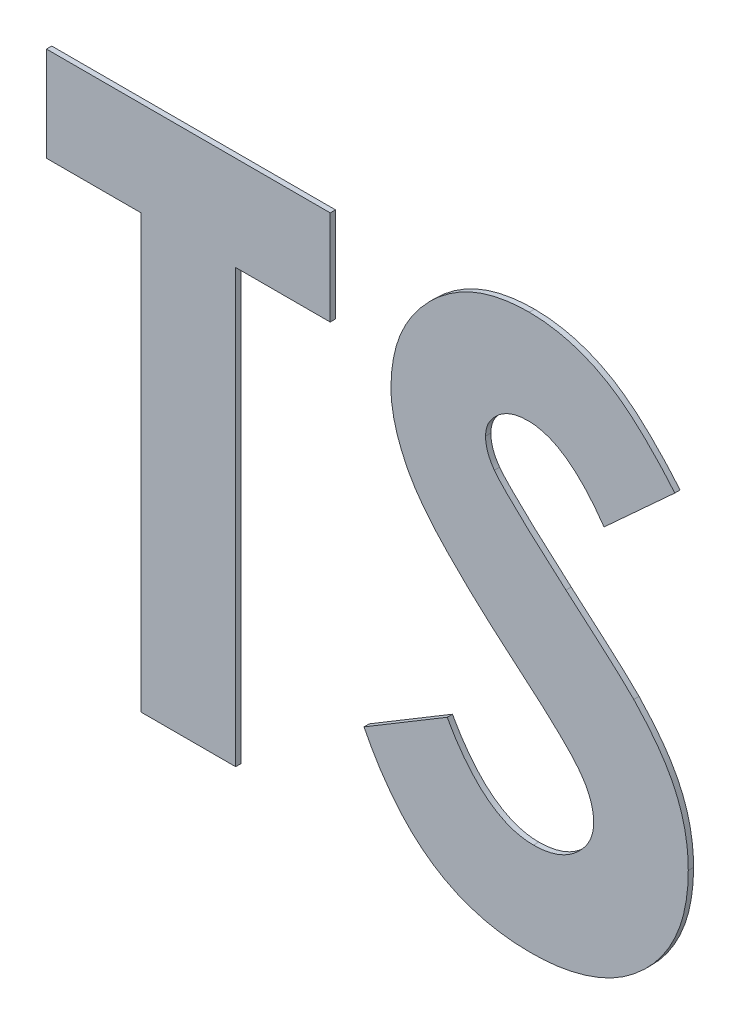
SolidWorks part; units mm, degrees
ref_plane "Front Plane" through (0, 0, 0) normal (0, 0, 1) x (1, 0, 0)
ref_plane "Top Plane" through (0, 0, 0) normal (0, 1, 0) x (1, 0, 0)
ref_plane "Right Plane" through (0, 0, 0) normal (1, 0, 0) x (0, 0, -1)
sketch "Sketch2" plane through (0, 0, 0) normal (0, 0, 1) x (1, 0, 0)
  line L0 (-12.5, 0) -> (12.5, 0)
  line L1 (-6.3462, 10) -> (-0.9615, 10)
  line L2 (-0.9615, 10) -> (-0.9615, 8.2051)
  line L3 (-0.9615, 8.2051) -> (-2.7564, 8.2051)
  line L4 (-2.7564, 8.2051) -> (-2.7564, 0)
  line L5 (-2.7564, 0) -> (-4.5513, 0)
  line L6 (-4.5513, 0) -> (-4.5513, 8.2051)
  line L7 (-4.5513, 8.2051) -> (-6.3462, 8.2051)
  line L8 (-6.3462, 8.2051) -> (-6.3462, 10)
  line L9 (5.5769, 8.6639) -> (4.2348, 7.4359)
  line L10 (-0.3205, 1.873) -> (1.258, 2.8205)
  spline S0 degree 3 poles (4.2348, 7.4359) (4.1274, 7.5935) (3.9586, 7.811) (3.7099, 8.059) (3.531, 8.2055) (3.3496, 8.3196) (3.1102, 8.4259) (2.9207, 8.4619) (2.7965, 8.4615) knots 0 0 0 0 0.311824 0.448433 0.573381 0.689077 0.797573 1 1 1 1
  spline S1 degree 3 poles (2.7965, 8.4615) (2.6872, 8.4617) (2.5244, 8.4422) (2.3335, 8.3511) (2.212, 8.2647) (2.1159, 8.1604) (2.0148, 8.0173) (1.9881, 7.8888) (1.9872, 7.8065) knots 0 0 0 0 0.285993 0.416634 0.54738 0.671583 0.784401 1 1 1 1
  spline S2 degree 3 poles (1.9872, 7.8065) (1.9859, 7.7225) (2.0179, 7.5513) (2.1012, 7.3986) (2.1534, 7.3277) knots 0 0 0 0 0.487115 1 1 1 1
  spline S3 degree 3 poles (2.1534, 7.3277) (2.2046, 7.2594) (2.3042, 7.1523) (2.4571, 6.9964) (2.6145, 6.8473) (2.7962, 6.6735) (3.0992, 6.4023) (3.34, 6.1871) (3.5116, 6.0377) knots 0 0 0 0 0.136349 0.233805 0.349411 0.483179 0.635967 1 1 1 1
  spline S4 degree 3 poles (3.5116, 6.0377) (3.6708, 5.899) (3.8991, 5.7042) (4.1821, 5.4542) (4.3571, 5.3001) (4.5049, 5.1667) (4.6501, 5.0308) (4.7456, 4.9393) (4.7997, 4.8838) knots 0 0 0 0 0.366184 0.520457 0.655012 0.770624 0.865677 1 1 1 1
  spline S5 degree 3 poles (4.7997, 4.8838) (4.972, 4.703) (5.2072, 4.4292) (5.4597, 4.0421) (5.6003, 3.7658) (5.7062, 3.4871) (5.8076, 3.0986) (5.8335, 2.7949) (5.8333, 2.5901) knots 0 0 0 0 0.289954 0.417139 0.535255 0.648751 0.762405 1 1 1 1
  spline S6 degree 3 poles (5.8333, 2.5901) (5.8366, 2.3918) (5.8074, 2.0997) (5.7236, 1.7235) (5.6289, 1.4615) (5.5132, 1.2106) (5.3683, 0.9748) (5.1982, 0.7517) (5.0031, 0.5453) (4.7874, 0.358) (4.556, 0.1913) (4.3066, 0.0536) (4.0415, -0.0597) (3.7607, -0.147) (3.3581, -0.2352) (3.0436, -0.2568) (2.8305, -0.2564) knots 0 0 0 0 0.127927 0.189047 0.248544 0.307607 0.367248 0.426963 0.488617 0.550392 0.611331 0.672556 0.734024 0.797341 0.86225 1 1 1 1
  spline S7 degree 3 poles (2.8305, -0.2564) (2.6612, -0.2563) (2.4104, -0.2415) (2.0849, -0.1877) (1.8527, -0.131) (1.6283, -0.0591) (1.4117, 0.0287) (1.2043, 0.1339) (1.0048, 0.2541) (0.8139, 0.3938) (0.6293, 0.5499) (0.4528, 0.725) (0.2836, 0.9186) (0.1228, 1.1312) (-0.0923, 1.4428) (-0.2305, 1.6979) (-0.3205, 1.873) knots 0 0 0 0 0.125868 0.18624 0.244977 0.303358 0.36123 0.418489 0.475937 0.534204 0.594059 0.655469 0.718772 0.784975 0.853522 1 1 1 1
  spline S8 degree 3 poles (1.258, 2.8205) (1.3655, 2.6242) (1.5403, 2.3522) (1.8114, 2.0406) (2.0144, 1.8585) (2.2242, 1.7157) (2.5109, 1.58) (2.7432, 1.5381) (2.8966, 1.5385) knots 0 0 0 0 0.307612 0.442139 0.566229 0.681222 0.789558 1 1 1 1
  spline S9 degree 3 poles (2.8966, 1.5385) (3.0475, 1.5373) (3.2697, 1.5716) (3.5386, 1.6928) (3.7094, 1.819) (3.8538, 1.9649) (3.9954, 2.1785) (4.0406, 2.3639) (4.0385, 2.486) knots 0 0 0 0 0.275473 0.404346 0.53543 0.661427 0.777867 1 1 1 1
  spline S10 degree 3 poles (4.0385, 2.486) (4.0382, 2.6022) (4.0031, 2.7792) (3.9021, 3.0036) (3.8111, 3.1449) (3.7183, 3.2632) (3.6297, 3.3657) (3.5217, 3.4789) (3.3947, 3.6031) (3.2503, 3.7392) (3.0239, 3.9465) (2.8406, 4.1029) (2.7123, 4.2107) knots 0 0 0 0 0.155091 0.238352 0.328404 0.379384 0.439618 0.509831 0.588875 0.677436 0.775547 1 1 1 1
  spline S11 degree 3 poles (2.7123, 4.2107) (2.4672, 4.4164) (2.1184, 4.7176) (1.6845, 5.1157) (1.4102, 5.3846) (1.1693, 5.6321) (0.9634, 5.8601) (0.7947, 6.0706) (0.6171, 6.3198) (0.4488, 6.6236) (0.2567, 7.1011) (0.1897, 7.4745) (0.1923, 7.7204) knots 0 0 0 0 0.215201 0.309902 0.395959 0.473447 0.54214 0.602523 0.654726 0.747804 0.835278 1 1 1 1
  spline S12 degree 3 poles (0.1923, 7.7204) (0.1913, 7.8891) (0.2166, 8.1393) (0.2939, 8.4619) (0.3766, 8.6917) (0.484, 8.9115) (0.6144, 9.1226) (0.7698, 9.323) (0.945, 9.5125) (1.1381, 9.6856) (1.3444, 9.8385) (1.5627, 9.9676) (1.7918, 10.0747) (2.0331, 10.1566) (2.3734, 10.2355) (2.6382, 10.2553) (2.8165, 10.2564) knots 0 0 0 0 0.124457 0.184841 0.244567 0.304319 0.3652 0.427421 0.491262 0.555499 0.618605 0.680495 0.742473 0.804991 0.868252 1 1 1 1
  spline S13 degree 3 poles (2.8165, 10.2564) (3.0513, 10.2563) (3.4034, 10.2122) (3.855, 10.0706) (4.1282, 9.9434) (4.3455, 9.82) (4.5121, 9.7064) (4.6816, 9.5763) (4.8554, 9.4292) (5.0302, 9.2623) (5.2786, 9.0119) (5.4585, 8.8078) (5.5769, 8.6639) knots 0 0 0 0 0.212977 0.319777 0.428556 0.485857 0.546559 0.611431 0.679821 0.753159 0.830753 1 1 1 1
  dimension "D1" = 25
extrude "Boss-Extrude2" add sketch "Sketch2" along normal blind 0.1 contours L8 L7 L6 L0 L4 L3 L2 L1 | S13 S12 S11 S10 S9 S8 L10 S7 L0 S6 S5 S4 S3 S2 S1 S0 L9 | S7 S6 L0
